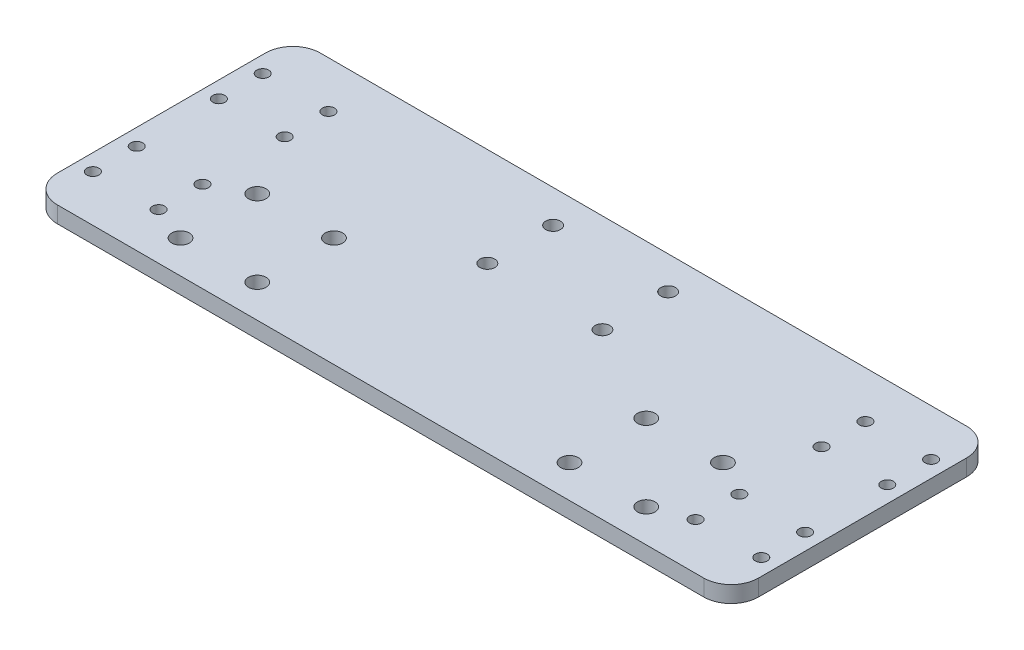
SolidWorks part; units mm, degrees
material "碳纤维"
ref_plane "前视基准面" through (0, 0, 0) normal (0, 0, 1) x (1, 0, 0)
ref_plane "上视基准面" through (0, 0, 0) normal (0, 1, 0) x (1, 0, 0)
ref_plane "右视基准面" through (0, 0, 0) normal (1, 0, 0) x (0, 0, -1)
sketch "草图1" plane through (0, 0, 0) normal (0, 1, 0) x (1, 0, 0)
  line L0 (0, 24) -> (128, 24) construction
  line L1 (0, 0) -> (128, 0)
  line L2 (0, 0) -> (0, 48)
  line L3 (0, 48) -> (18, 48)
  line L4 (128, 0) -> (128, 48)
  line L5 (64, 50) -> (64, 0) construction
  line L6 (113, 8.5) -> (125, 8.5) construction
  line L7 (125, 16.5) -> (125, 8.5) construction
  line L8 (113, 16.5) -> (113, 8.5) construction
  line L9 (113, 16.5) -> (125, 16.5) construction
  line L13 (110, 48) -> (128, 48)
  line L14 (119, 8.5) -> (119, 48) construction
  line L19 (18, 48) -> (110, 48)
  circle A0 centre (125, 8.5) radius 1.1
  circle A1 centre (113, 8.5) radius 1.1
  circle A2 centre (125, 16.5) radius 1.1
  circle A3 centre (113, 16.5) radius 1.1
  circle A4 centre (125, 31.5) radius 1.1
  circle A5 centre (125, 39.5) radius 1.1
  circle A6 centre (113, 39.5) radius 1.1
  circle A7 centre (113, 31.5) radius 1.1
  circle A8 centre (15, 8.5) radius 1.1
  circle A9 centre (3, 8.5) radius 1.1
  circle A10 centre (3, 16.5) radius 1.1
  circle A11 centre (15, 16.5) radius 1.1
  circle A12 centre (15, 39.5) radius 1.1
  circle A13 centre (3, 39.5) radius 1.1
  circle A14 centre (3, 31.5) radius 1.1
  circle A15 centre (15, 31.5) radius 1.1
  dimension "D3" = 2.2
  dimension "D6" = 122
  dimension "D7" = 15
  dimension "D1" = 128
  dimension "D2" = 48
  dimension "D4" = 12
  dimension "D5" = 8
extrude "凸台-拉伸1" add sketch "草图1" along normal blind 3
sketch "草图2" plane through (0, 3, 0) normal (0, 1, 0) x (1, 0, 0)
  line L0 (21.5, 20) -> (21.5, 6) construction
  line L1 (21.5, 20) -> (35.5, 20) construction
  line L2 (35.5, 20) -> (35.5, 6) construction
  line L3 (35.5, 6) -> (21.5, 6) construction
  line L4 (64, 48) -> (64, 0) construction
  line L6 (0, 0) -> (128, 0) construction
  line L7 (92.5, 6) -> (106.5, 6) construction
  line L8 (92.5, 20) -> (92.5, 6) construction
  line L9 (106.5, 20) -> (92.5, 20) construction
  line L10 (106.5, 20) -> (106.5, 6) construction
  line L11 (128, 48) -> (0, 48) construction
  circle A16 centre (21.5, 20) radius 1.6
  circle A17 centre (35.5, 20) radius 1.6
  circle A18 centre (35.5, 6) radius 1.6
  circle A19 centre (21.5, 6) radius 1.6
  circle A20 centre (106.5, 6) radius 1.6
  circle A21 centre (92.5, 6) radius 1.6
  circle A22 centre (92.5, 20) radius 1.6
  circle A23 centre (106.5, 20) radius 1.6
  dimension "D1" = 3.2
  dimension "D2" = 14
  dimension "D3" = 14
  dimension "D4" = 57
  dimension "D5" = 6
extrude "切除-拉伸1" cut sketch "草图2" against normal through all
sketch "草图5" plane through (0, 3, 0) normal (0, 1, 0) x (1, 0, 0)
  line L0 (64, 48) -> (64, 0) construction
  line L1 (128, 48) -> (0, 48) construction
  line L2 (0, 0) -> (128, 0) construction
  line L3 (64, 36) -> (66.7201, 36) construction
  circle A0 centre (53.5, 42) radius 1.35
  circle A1 centre (74.5, 42) radius 1.35
  circle A2 centre (74.5, 30) radius 1.35
  circle A3 centre (53.5, 30) radius 1.35
  dimension "D1" = 2.7
  dimension "D3" = 12
  dimension "D4" = 21
  dimension "D2" = 12
extrude "切除-拉伸3" cut sketch "草图5" against normal through all
sketch "草图3" [suppressed] plane through (0, 3, 0) normal (0, 1, 0) x (1, 0, 0)
  line L0 (80, 0) -> (80, 72) construction
  line L1 (0, 0) -> (160, 0) construction
  line L2 (160, 48) -> (0, 48) construction
  line L3 (69.5, 42) -> (69.5, 30) construction
  line L4 (80, 36) -> (102.0333, 36) construction
  line L5 (69.5, 30) -> (90.5, 30) construction
  line L6 (139, 48) -> (139, 0) construction
  line L7 (137.45, 43.5) -> (137.45, 27.5) construction
  line L8 (135.9, 43.5) -> (139, 43.5)
  line L9 (135.9, 41.5) -> (135.9, 29.5)
  line L10 (135.9, 27.5) -> (139, 27.5)
  line L11 (139, 41.5) -> (139, 29.5)
  line L12 (135.9, 35.5) -> (139, 35.5) construction
  line L13 (135.9, 43.5) -> (135.9, 41.5) construction
  line L14 (135.9, 29.5) -> (135.9, 27.5) construction
  line L15 (160, 24) -> (139, 24) construction
  line L16 (160, 0) -> (160, 48) construction
  line L17 (135.9, 4.5) -> (139, 4.5)
  line L18 (135.9, 6.5) -> (135.9, 18.5)
  line L19 (135.9, 20.5) -> (139, 20.5)
  line L20 (139, 6.5) -> (139, 18.5)
  line L21 (133, 48) -> (133, 0) construction
  line L22 (127, 6.5) -> (127, 18.5)
  line L23 (130.1, 20.5) -> (127, 20.5)
  line L24 (130.1, 6.5) -> (130.1, 18.5)
  line L25 (130.1, 4.5) -> (127, 4.5)
  line L26 (130.1, 43.5) -> (127, 43.5)
  line L27 (130.1, 41.5) -> (130.1, 29.5)
  line L28 (130.1, 27.5) -> (127, 27.5)
  line L29 (127, 41.5) -> (127, 29.5)
  line L30 (122.5, 20) -> (108.5, 20) construction
  line L31 (115.5, 20) -> (115.5, 48) construction
  line L32 (100.9, 4.5) -> (104, 4.5)
  line L33 (100.9, 6.5) -> (100.9, 18.5)
  line L34 (100.9, 20.5) -> (104, 20.5)
  line L35 (104, 6.5) -> (104, 18.5)
  line L36 (104, 41.5) -> (104, 29.5)
  line L37 (100.9, 27.5) -> (104, 27.5)
  line L38 (100.9, 41.5) -> (100.9, 29.5)
  line L39 (100.9, 43.5) -> (104, 43.5)
  line L40 (24.1, 43.5) -> (21, 43.5)
  line L41 (24.1, 41.5) -> (24.1, 29.5)
  line L42 (24.1, 27.5) -> (21, 27.5)
  line L43 (21, 41.5) -> (21, 29.5)
  line L44 (33, 41.5) -> (33, 29.5)
  line L45 (29.9, 27.5) -> (33, 27.5)
  line L46 (29.9, 41.5) -> (29.9, 29.5)
  line L47 (29.9, 43.5) -> (33, 43.5)
  line L48 (21, 6.5) -> (21, 18.5)
  line L49 (24.1, 20.5) -> (21, 20.5)
  line L50 (24.1, 6.5) -> (24.1, 18.5)
  line L51 (24.1, 4.5) -> (21, 4.5)
  line L52 (29.9, 4.5) -> (33, 4.5)
  line L53 (29.9, 6.5) -> (29.9, 18.5)
  line L54 (29.9, 20.5) -> (33, 20.5)
  line L55 (33, 6.5) -> (33, 18.5)
  line L56 (56, 6.5) -> (56, 18.5)
  line L57 (59.1, 20.5) -> (56, 20.5)
  line L58 (59.1, 6.5) -> (59.1, 18.5)
  line L59 (59.1, 4.5) -> (56, 4.5)
  line L60 (59.1, 43.5) -> (56, 43.5)
  line L61 (59.1, 41.5) -> (59.1, 29.5)
  line L62 (59.1, 27.5) -> (56, 27.5)
  line L63 (56, 41.5) -> (56, 29.5)
  circle A0 centre (90.5, 30) radius 1.35 construction
  arc A1 (135.9, 43.5) -> (135.9, 41.5) centre (135.9, 42.5) ccw
  arc A2 (139, 41.5) -> (139, 43.5) centre (139, 42.5) ccw
  arc A3 (139, 29.5) -> (139, 27.5) centre (139, 28.5) cw
  circle A8 centre (69.5, 42) radius 1.35 construction
  circle A10 centre (90.5, 42) radius 1.35 construction
  circle A14 centre (69.5, 30) radius 1.35 construction
  arc A15 (135.9, 27.5) -> (135.9, 29.5) centre (135.9, 28.5) cw
  arc A16 (139, 6.5) -> (139, 4.5) centre (139, 5.5) cw
  arc A17 (135.9, 4.5) -> (135.9, 6.5) centre (135.9, 5.5) cw
  arc A18 (135.9, 20.5) -> (135.9, 18.5) centre (135.9, 19.5) ccw
  arc A19 (139, 18.5) -> (139, 20.5) centre (139, 19.5) ccw
  arc A20 (127, 18.5) -> (127, 20.5) centre (127, 19.5) cw
  arc A21 (130.1, 20.5) -> (130.1, 18.5) centre (130.1, 19.5) cw
  arc A22 (130.1, 4.5) -> (130.1, 6.5) centre (130.1, 5.5) ccw
  arc A23 (127, 6.5) -> (127, 4.5) centre (127, 5.5) ccw
  arc A24 (127, 41.5) -> (127, 43.5) centre (127, 42.5) cw
  arc A25 (130.1, 43.5) -> (130.1, 41.5) centre (130.1, 42.5) cw
  arc A26 (130.1, 27.5) -> (130.1, 29.5) centre (130.1, 28.5) ccw
  arc A27 (127, 29.5) -> (127, 27.5) centre (127, 28.5) ccw
  arc A28 (104, 6.5) -> (104, 4.5) centre (104, 5.5) cw
  arc A29 (100.9, 4.5) -> (100.9, 6.5) centre (100.9, 5.5) cw
  arc A30 (100.9, 20.5) -> (100.9, 18.5) centre (100.9, 19.5) ccw
  arc A31 (104, 18.5) -> (104, 20.5) centre (104, 19.5) ccw
  arc A32 (104, 29.5) -> (104, 27.5) centre (104, 28.5) cw
  arc A33 (100.9, 27.5) -> (100.9, 29.5) centre (100.9, 28.5) cw
  arc A34 (100.9, 43.5) -> (100.9, 41.5) centre (100.9, 42.5) ccw
  arc A35 (104, 41.5) -> (104, 43.5) centre (104, 42.5) ccw
  arc A36 (21, 41.5) -> (21, 43.5) centre (21, 42.5) cw
  arc A37 (24.1, 43.5) -> (24.1, 41.5) centre (24.1, 42.5) cw
  arc A38 (24.1, 27.5) -> (24.1, 29.5) centre (24.1, 28.5) ccw
  arc A39 (21, 29.5) -> (21, 27.5) centre (21, 28.5) ccw
  arc A40 (33, 29.5) -> (33, 27.5) centre (33, 28.5) cw
  arc A41 (29.9, 27.5) -> (29.9, 29.5) centre (29.9, 28.5) cw
  arc A42 (29.9, 43.5) -> (29.9, 41.5) centre (29.9, 42.5) ccw
  arc A43 (33, 41.5) -> (33, 43.5) centre (33, 42.5) ccw
  arc A44 (21, 18.5) -> (21, 20.5) centre (21, 19.5) cw
  arc A45 (24.1, 20.5) -> (24.1, 18.5) centre (24.1, 19.5) cw
  arc A46 (24.1, 4.5) -> (24.1, 6.5) centre (24.1, 5.5) ccw
  arc A47 (21, 6.5) -> (21, 4.5) centre (21, 5.5) ccw
  arc A48 (33, 6.5) -> (33, 4.5) centre (33, 5.5) cw
  arc A49 (29.9, 4.5) -> (29.9, 6.5) centre (29.9, 5.5) cw
  arc A50 (29.9, 20.5) -> (29.9, 18.5) centre (29.9, 19.5) ccw
  arc A51 (33, 18.5) -> (33, 20.5) centre (33, 19.5) ccw
  arc A52 (56, 18.5) -> (56, 20.5) centre (56, 19.5) cw
  arc A53 (59.1, 20.5) -> (59.1, 18.5) centre (59.1, 19.5) cw
  arc A54 (59.1, 4.5) -> (59.1, 6.5) centre (59.1, 5.5) ccw
  arc A55 (56, 6.5) -> (56, 4.5) centre (56, 5.5) ccw
  arc A56 (56, 41.5) -> (56, 43.5) centre (56, 42.5) cw
  arc A57 (59.1, 43.5) -> (59.1, 41.5) centre (59.1, 42.5) cw
  arc A58 (59.1, 27.5) -> (59.1, 29.5) centre (59.1, 28.5) ccw
  arc A59 (56, 29.5) -> (56, 27.5) centre (56, 28.5) ccw
  dimension "D1" = 2.7
  dimension "D3" = 12
  dimension "D4" = 12
  dimension "D6" = 1
  dimension "D2" = 21
  dimension "D5" = 3.1
  dimension "D7" = 8
  dimension "D8" = 7
  dimension "D9" = 21
  dimension "D10" = 27
extrude "切除-拉伸2" [suppressed] cut sketch "草图3" against normal through all
fillet "圆角1" radius 5 4 edges at (128, 1.5, -48) (128, 1.5, 0) (0, 1.5, 0) (0, 1.5, -48)
sketch "草图4" [suppressed] plane through (135.9, 0, 0) normal (1, 0, 0) x (0, 0, -1)
  line L2 (43.5, 0) -> (43.5, 3) construction
  line L6 (27.5, 3) -> (27.5, 0) construction
  line L10 (20.5, 0) -> (20.5, 3) construction
  line L14 (4.5, 3) -> (4.5, 0) construction
  line L18 (43.5, 0) -> (43.5, 3)
  line L22 (27.5, 3) -> (27.5, 0)
  line L26 (20.5, 0) -> (20.5, 3)
  line L30 (4.5, 3) -> (4.5, 0)
  line L32 (4.5, 0) -> (4.5, -3)
  line L33 (4.5, -3) -> (20.5, -3)
  line L34 (20.5, -3) -> (20.5, 0)
  line L35 (27.5, 0) -> (27.5, -3)
  line L36 (27.5, -3) -> (43.5, -3)
  line L37 (43.5, -3) -> (43.5, 0)
  line L38 (45.5, 3) -> (49, 3)
  line L39 (0, 3) -> (2.5, 3)
  line L41 (1, 7) -> (49, 7)
  line L42 (49, 3) -> (49, 7)
  line L43 (22.5, 3) -> (25.5, 3)
  line L44 (1, 7) -> (-1, 7)
  line L45 (-1, 7) -> (-1, 3)
  line L46 (-1, 3) -> (0, 3)
  line L47 (0, 0) -> (0, 3) construction
  line L48 (48, 3) -> (48, 0) construction
  arc A0 (4.5, 3) -> (2.5, 3) centre (3.5, 3) ccw
  arc A1 (22.5, 3) -> (20.5, 3) centre (21.5, 3) ccw
  arc A2 (27.5, 3) -> (25.5, 3) centre (26.5, 3) ccw
  arc A3 (45.5, 3) -> (43.5, 3) centre (44.5, 3) ccw
  dimension "D4" = 2
  dimension "D1" = 6
  dimension "D3" = 4
  dimension "D5" = 1
  dimension "D6" = 1
extrude "凸台-拉伸2" [suppressed] add sketch "草图4" along normal blind 3 separate body
chamfer "倒角1" [suppressed] distance 1 angle 45
pattern_linear "阵列(线性)1" [suppressed] count 2 spacing 9
pattern_linear "阵列(线性)2" [suppressed] count 2 spacing 26
ref_plane "基准面1" through (64, 0, 0) normal (-1, 0, 0) x (0, 0, 1)
mirror "镜向1" [suppressed] about plane through (64, 0, 0) normal (-1, 0, 0)
